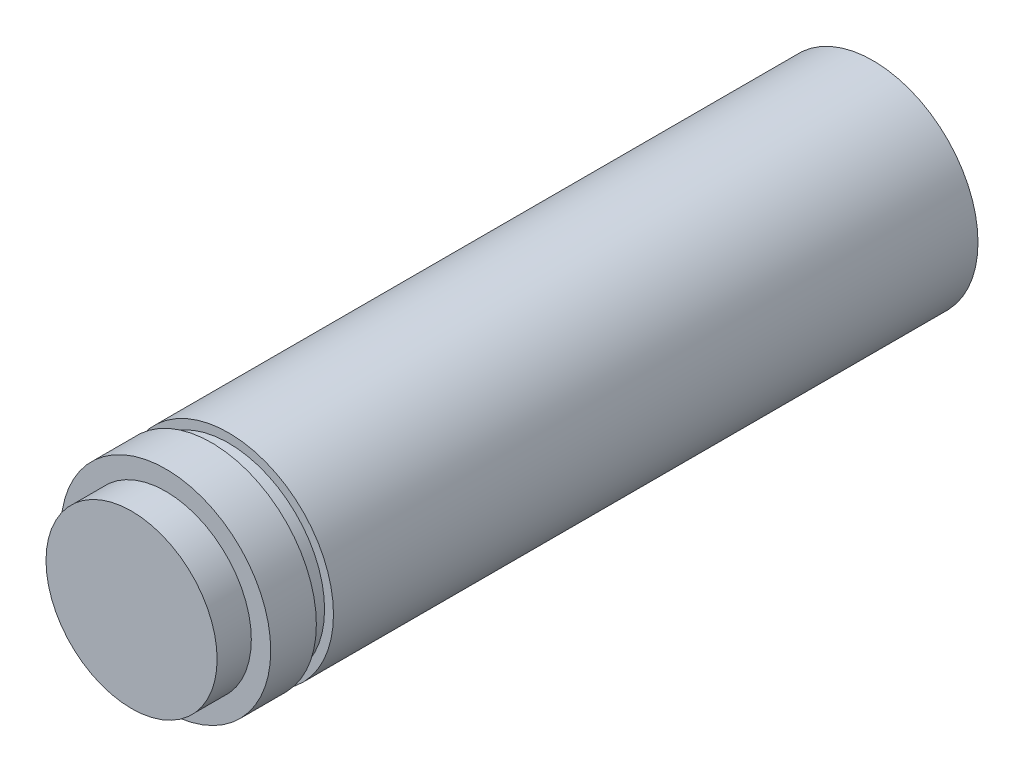
SolidWorks part; units mm, degrees
material "Batteries"
ref_plane "Front Plane" through (0, 0, 0) normal (0, 0, 1) x (1, 0, 0)
ref_plane "Top Plane" through (0, 0, 0) normal (0, 1, 0) x (1, 0, 0)
ref_plane "Right Plane" through (0, 0, 0) normal (1, 0, 0) x (0, 0, -1)
sketch "Sketch1" plane through (0, 0, 0) normal (0, 0, 1) x (1, 0, 0)
  circle A0 centre (0, 0) radius 9.2
  dimension "D1" = 18.4
extrude "Boss-Extrude1" add sketch "Sketch1" along normal blind 65
sketch "Sketch2" plane through (0, 0, 65) normal (0, 0, 1) x (1, 0, 0)
  circle A0 centre (0, 0) radius 7.5
  circle A1 centre (0, 0) radius 9.2
  dimension "D1" = 15
extrude "Cut-Extrude2" cut sketch "Sketch2" against normal blind 3
ref_plane "Plane1" through (0, 0, 58) normal (0, 0, 1) x (1, 0, 0)
sketch "Sketch3" plane through (0, 0, 58) normal (0, 0, 1) x (1, 0, 0)
  circle A0 centre (0, 0) radius 9.2
  circle A1 centre (0, 0) radius 8.4196
extrude "Cut-Extrude3" cut sketch "Sketch3" against normal blind 1.5
